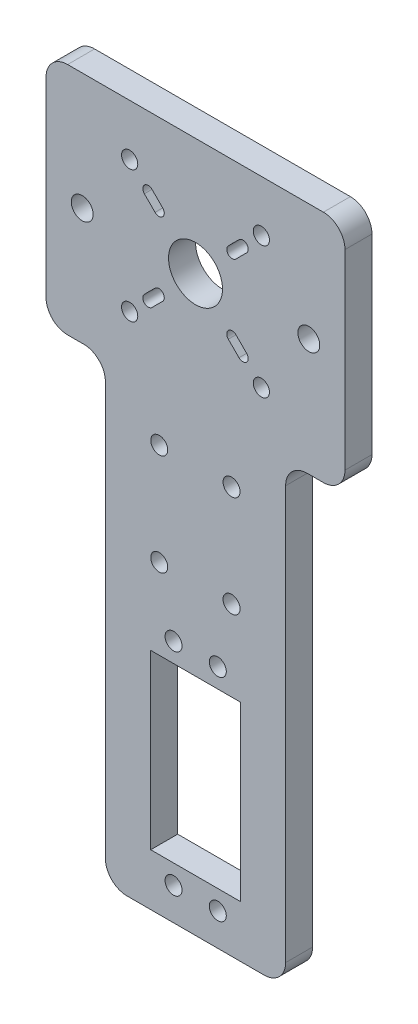
SolidWorks part; units mm, degrees
ref_plane "Front Plane" through (0, 0, 0) normal (0, 0, 1) x (1, 0, 0)
ref_plane "Top Plane" through (0, 0, 0) normal (0, 1, 0) x (1, 0, 0)
ref_plane "Right Plane" through (0, 0, 0) normal (1, 0, 0) x (0, 0, -1)
sketch "Sketch1" plane through (0, 0, 0) normal (0, 0, 1) x (1, 0, 0)
  line L0 (0, 0) -> (0, 11.938) construction
  line L3 (-16.129, -83.74) -> (16.129, -83.74)
  line L5 (-21.209, 78.74) -> (21.209, -78.74) construction
  line L6 (-21.209, -78.74) -> (21.209, 78.74) construction
  line L7 (0, 11.938) -> (8.4836, 11.938) construction
  line L8 (0, 0) -> (0, 51.181) construction
  line L9 (0, 51.181) -> (15.494, 51.181) construction
  line L10 (15.494, 51.181) -> (15.494, 66.675) construction
  line L11 (0, 51.181) -> (9.8783, 61.0593) construction
  line L12 (8.621, 59.802) -> (11.1355, 62.3165) construction
  line L13 (7.723, 60.7001) -> (10.2375, 63.2145)
  line L14 (9.5191, 58.904) -> (12.0335, 61.4185)
  line L17 (-8.621, 59.802) -> (-11.1355, 62.3165) construction
  line L20 (-9.5191, 58.904) -> (-12.0335, 61.4185)
  line L23 (-7.723, 60.7001) -> (-10.2375, 63.2145)
  line L24 (0, 0) -> (0, -26.32) construction
  line L25 (0, -26.32) -> (-5.1689, -26.32) construction
  line L26 (0, -26.32) -> (0, -51.212) construction
  line L27 (0, 51.181) -> (-26.67, 51.181) construction
  line L28 (-10.541, -30.892) -> (10.541, -30.892)
  line L29 (-10.541, -30.892) -> (-10.541, -71.532)
  line L30 (-10.541, -71.532) -> (10.541, -71.532)
  line L31 (10.541, -30.892) -> (10.541, -71.532)
  line L32 (-10.541, -30.892) -> (10.541, -71.532) construction
  line L33 (-10.541, -71.532) -> (10.541, -30.892) construction
  line L34 (-8.621, 42.56) -> (-11.1355, 40.0455) construction
  line L35 (-7.723, 41.6619) -> (-10.2375, 39.1475)
  line L36 (-9.5191, 43.458) -> (-12.0335, 40.9435)
  line L37 (8.621, 42.56) -> (11.1355, 40.0455) construction
  line L38 (9.5191, 43.458) -> (12.0335, 40.9435)
  line L39 (7.723, 41.6619) -> (10.2375, 39.1475)
  line L40 (-21.209, 18.542) -> (-21.209, -78.66)
  line L41 (-30.099, 23.622) -> (-26.289, 23.622)
  line L42 (-35.179, 28.702) -> (-35.179, 73.66)
  line L43 (-30.099, 78.74) -> (30.099, 78.74)
  line L44 (35.179, 28.702) -> (35.179, 73.66)
  line L45 (-35.179, 23.622) -> (35.179, 78.74) construction
  line L46 (-35.179, 78.74) -> (35.179, 23.622) construction
  line L47 (21.209, 18.542) -> (21.209, -78.66)
  line L48 (26.289, 23.622) -> (30.099, 23.622)
  circle A0 centre (8.4836, 11.938) radius 2
  circle A1 centre (-8.5344, 11.938) radius 2
  circle A2 centre (-8.5344, -11.938) radius 2
  circle A3 centre (8.4836, -11.938) radius 2
  circle A4 centre (0, 51.181) radius 6.35
  circle A5 centre (15.494, 66.675) radius 1.905
  circle A6 centre (-15.494, 66.675) radius 1.905
  circle A7 centre (-15.494, 35.687) radius 1.905
  circle A8 centre (15.494, 35.687) radius 1.905
  arc A9 (7.723, 60.7001) -> (9.5191, 58.904) centre (8.621, 59.802) ccw
  arc A10 (12.0335, 61.4185) -> (10.2375, 63.2145) centre (11.1355, 62.3165) ccw
  circle A17 centre (-5.1689, -26.32) radius 2
  circle A18 centre (5.2451, -26.32) radius 2
  circle A19 centre (5.2451, -76.104) radius 2
  circle A20 centre (-5.1689, -76.104) radius 2
  circle A21 centre (-26.67, 51.181) radius 2.575
  arc A22 (-9.5191, 58.904) -> (-7.723, 60.7001) centre (-8.621, 59.802) ccw
  arc A23 (-10.2375, 63.2145) -> (-12.0335, 61.4185) centre (-11.1355, 62.3165) ccw
  arc A24 (-7.723, 41.6619) -> (-9.5191, 43.458) centre (-8.621, 42.56) ccw
  arc A25 (-12.0335, 40.9435) -> (-10.2375, 39.1475) centre (-11.1355, 40.0455) ccw
  arc A26 (9.5191, 43.458) -> (7.723, 41.6619) centre (8.621, 42.56) ccw
  arc A27 (10.2375, 39.1475) -> (12.0335, 40.9435) centre (11.1355, 40.0455) ccw
  circle A28 centre (26.67, 51.181) radius 2.575
  arc A29 (-21.209, -78.66) -> (-16.129, -83.74) centre (-16.129, -78.66) ccw
  arc A30 (16.129, -83.74) -> (21.209, -78.66) centre (16.129, -78.66) ccw
  arc A31 (-30.099, 23.622) -> (-35.179, 28.702) centre (-30.099, 28.702) cw
  arc A32 (-21.209, 18.542) -> (-26.289, 23.622) centre (-26.289, 18.542) ccw
  arc A33 (21.209, 18.542) -> (26.289, 23.622) centre (26.289, 18.542) cw
  arc A34 (30.099, 23.622) -> (35.179, 28.702) centre (30.099, 28.702) ccw
  arc A35 (30.099, 78.74) -> (35.179, 73.66) centre (30.099, 73.66) cw
  arc A36 (-35.179, 73.66) -> (-30.099, 78.74) centre (-30.099, 73.66) cw
  point P0 (0, 0)
  point P30 (9.8783, 61.0593)
  point P43 (-9.8783, 61.0593)
  point P50 (-9.8783, 41.3027)
  point P57 (9.8783, 41.3027)
  point P59 (2.5264, 53.7074)
  point P76 (0, 51.181)
  dimension "D3" = 4
  dimension "D6" = 12.7
  dimension "D9" = 3.81
  dimension "D15" = 1.27
  dimension "D27" = 4
  dimension "D30" = 5.15
  dimension "D11" = 5.08
  dimension "D1" = 11.938
  dimension "D2" = 8.4836
  dimension "D5" = 51.181
  dimension "D7" = 15.494
  dimension "D8" = 15.494
  dimension "D13" = 97.202
  dimension "D14" = 45
  dimension "D16" = 1.778
  dimension "D17" = 13.97
  dimension "D19" = 26.32
  dimension "D20" = 5.1689
  dimension "D23" = 24.892
  dimension "D24" = 40.64
  dimension "D25" = 21.082
  dimension "D28" = 70.358
  dimension "D29" = 26.67
  dimension "D26" = 2
  dimension "D4" = 2
  dimension "D12" = 2
  dimension "D10" = 2
  dimension "D21" = 2
  dimension "D22" = 2
  dimension "D18" = 4
extrude "Boss-Extrude1" add sketch "Sketch1" along normal mid plane 6.35
